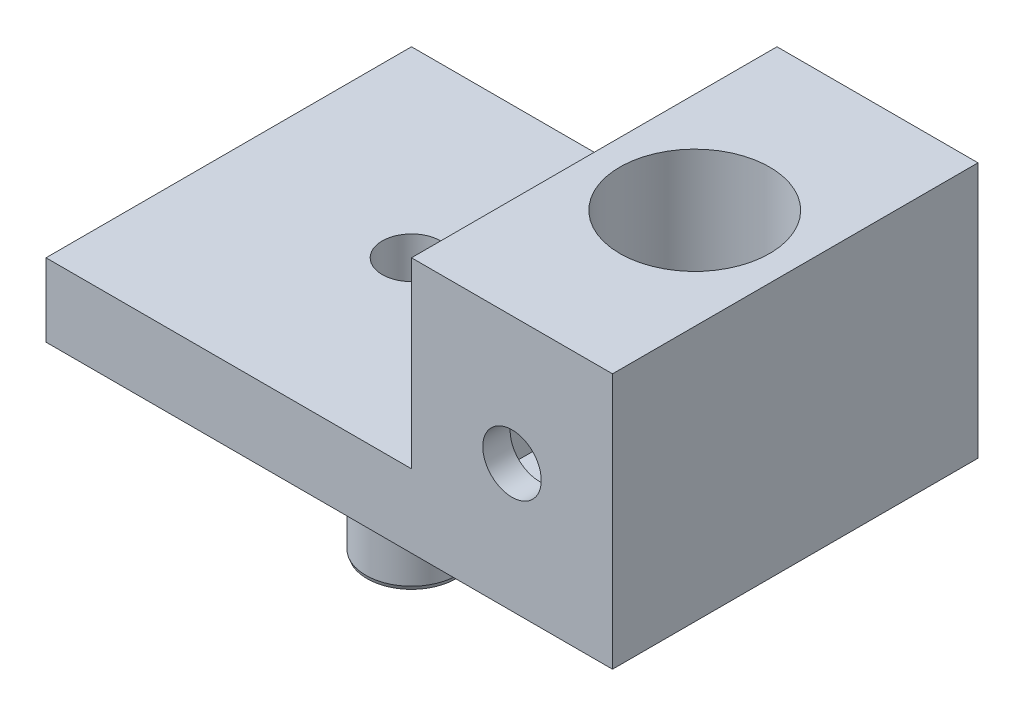
SolidWorks part; units mm, degrees
ref_plane "前视基准面" through (0, 0, 0) normal (0, 0, 1) x (1, 0, 0)
ref_plane "上视基准面" through (0, 0, 0) normal (0, 1, 0) x (1, 0, 0)
ref_plane "右视基准面" through (0, 0, 0) normal (1, 0, 0) x (0, 0, -1)
other "Configuration Table"
sketch "草图1" plane through (0, 0, 0) normal (0, 0, 1) x (1, 0, 0)
  line L0 (0, 0) -> (20, 0)
  line L1 (20, 0) -> (20, 10)
  line L2 (20, 10) -> (31, 10)
  line L3 (31, 10) -> (31, -4)
  line L4 (31, -4) -> (0, -4)
  line L5 (0, -4) -> (0, 0)
  dimension "D1" = 11
  dimension "D2" = 10
  dimension "D3" = 4
  dimension "D4" = 20
extrude "凸台-拉伸1" add sketch "草图1" along normal blind 20
hole_wizard "孔2" positions "草图5" profile "草图6" legacy end condition through all
sketch "草图5" plane through (0, 10, 0) normal (0, 1, 0) x (1, 0, 0)
  line L0 (25.5, 0) -> (25.5, -20) construction
  line L1 (31, 0) -> (20, 0) construction
  line L2 (31, -20) -> (20, -20) construction
  point P0 (25.5, -10)
sketch "草图6" plane through (25.5, 10, 10) normal (1, 0, 0) x (0, 0, 1)
  line L0 (0, 0) -> (0, 14)
  line L1 (0, 14) -> (4.1, 14)
  line L2 (4.1, 14) -> (4.1, 0)
  line L3 (4.1, 0) -> (0, 0)
  line L4 (0, 110) -> (0, -10) construction
  dimension "直径" = 8.2
  dimension "深度" = 14
ref_plane "基准面1" through (0, 0, 17) normal (0, 0, 1) x (1, 0, 0)
sketch "草图7" plane through (0, 0, 17) normal (0, 0, 1) x (1, 0, 0)
  line L0 (25.5, 10) -> (25.5, -4) construction
  line L1 (31, 10) -> (20, 10) construction
  line L2 (0, -4) -> (31, -4) construction
  line L4 (22.5, 0) -> (28.5, 0)
  line L5 (22.5, 0) -> (22.5, 6)
  line L6 (22.5, 6) -> (28.5, 6)
  line L7 (28.5, 0) -> (28.5, 6)
  line L8 (22.5, 0) -> (28.5, 6) construction
  line L9 (22.5, 6) -> (28.5, 0) construction
  point P6 (25.5, 3)
  dimension "D1" = 6
  dimension "D2" = 6
extrude "切除-拉伸1" cut sketch "草图7" against normal mid plane 3 contours L5 L4 L7 L6
hole_wizard "孔3" positions "草图8" profile "草图9" legacy
sketch "草图8" plane through (0, 0, 20) normal (0, 0, 1) x (1, 0, 0)
  line L0 (25.5, 10) -> (25.5, -4) construction
  line L1 (31, 10) -> (20, 10) construction
  line L2 (0, -4) -> (31, -4) construction
  line L4 (25.5, 3) -> (31, 3) construction
  line L5 (31, -4) -> (31, 10) construction
  point P0 (25.5, 3)
sketch "草图9" plane through (25.5, 3, 20) normal (1, 0, 0) x (0, -1, 0)
  line L0 (0, 0) -> (0, 7)
  line L1 (0, 7) -> (1.6, 7)
  line L2 (1.6, 7) -> (1.6, 0)
  line L3 (1.6, 0) -> (0, 0)
  line L4 (0, 110) -> (0, -10) construction
  dimension "直径" = 3.2
  dimension "深度" = 7
sketch "草图11" plane through (0, -4, 0) normal (0, -1, 0) x (1, 0, 0)
  line L0 (10, 20) -> (10, 0) construction
  line L1 (0, 20) -> (31, 20) construction
  line L2 (0, 0) -> (31, 0) construction
  line L3 (0, 20) -> (0, 0) construction
  circle A0 centre (10, 10) radius 2.5
  dimension "D2" = 5
  dimension "D1" = 10
extrude "凸台-拉伸2" add sketch "草图11" along normal blind 10
hole_wizard "孔4" positions "草图12" profile "草图13" legacy end condition through all
sketch "草图12" plane through (0, -14, 0) normal (0, -1, 0) x (-1, 0, 0)
  point P0 (-10, -10)
sketch "草图13" plane through (10, -14, 10) normal (1, 0, 0) x (0, 0, -1)
  line L0 (0, 0) -> (0, 24)
  line L1 (0, 24) -> (1.6, 24)
  line L2 (1.6, 24) -> (1.6, 0)
  line L3 (1.6, 0) -> (0, 0)
  line L4 (0, 110) -> (0, -10) construction
  dimension "直径" = 3.2
  dimension "深度" = 24
sketch "草图14" plane through (0, -4, 0) normal (0, -1, 0) x (1, 0, 0)
  circle A0 centre (10, 10) radius 2.8
  dimension "D1" = 5.6
extrude "凸台-拉伸3" add sketch "草图14" along normal blind 0.6
chamfer "倒角1" distance 0.2 angle 20 1 edges at (12.5, -14, 10)
hole_wizard "孔5" positions "草图15" profile "草图16" legacy end condition through all
sketch "草图15" plane through (0, 0, 0) normal (0, 1, 0) x (1, 0, 0)
  point P0 (10, -10)
sketch "草图16" plane through (10, 0, 10) normal (1, 0, 0) x (0, 0, 1)
  line L0 (0, 0) -> (0, 14)
  line L1 (0, 14) -> (1.6, 14)
  line L2 (1.6, 14) -> (1.6, 0)
  line L3 (1.6, 0) -> (0, 0)
  line L4 (0, 110) -> (0, -10) construction
  dimension "直径" = 3.2
  dimension "深度" = 14
